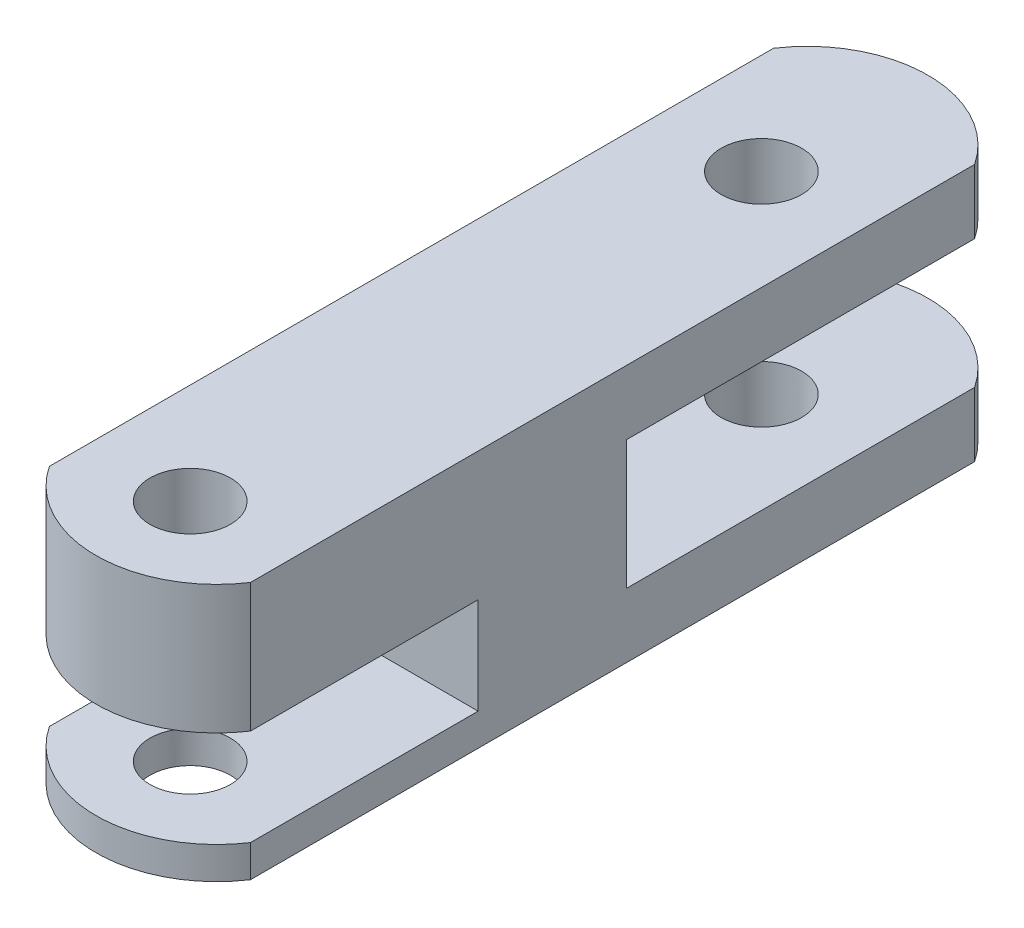
SolidWorks part; units mm, degrees
ref_plane "前视基准面" through (0, 0, 0) normal (0, 0, 1) x (1, 0, 0)
ref_plane "上视基准面" through (0, 0, 0) normal (0, 1, 0) x (1, 0, 0)
ref_plane "右视基准面" through (0, 0, 0) normal (1, 0, 0) x (0, 0, -1)
sketch "草图1" plane through (0, 0, 0) normal (0, 1, 0) x (1, 0, 0)
  line L1 (-12.5, 45) -> (12.5, 45) construction
  line L2 (-12.5, 45) -> (-12.5, -45)
  line L3 (-12.5, -45) -> (12.5, -45) construction
  line L4 (12.5, 45) -> (12.5, -45)
  line L5 (-12.5, 45) -> (12.5, -45) construction
  line L6 (-12.5, -45) -> (12.5, 45) construction
  arc A0 (-12.5, 45) -> (12.5, 45) centre (0, 36.7084) cw
  arc A1 (-12.5, -45) -> (12.5, -45) centre (0, -36.7084) ccw
  point P0 (0, 0)
  dimension "D3" = 15
  dimension "D1" = 90
  dimension "D2" = 25
extrude "凸台-拉伸1" add sketch "草图1" along normal mid plane 32
sketch "草图2" plane through (12.5, 0, 0) normal (1, 0, 0) x (0, 0, -1)
  line L0 (-45, 16) -> (-45, -16) construction
  line L1 (-16.7084, 0) -> (-73.2916, 0)
  line L2 (-16.7084, 0) -> (-16.7084, -12)
  line L3 (-16.7084, -12) -> (-73.2916, -12)
  line L4 (-73.2916, 0) -> (-73.2916, -12)
  line L5 (-16.7084, 0) -> (-73.2916, -12) construction
  line L6 (-16.7084, -12) -> (-73.2916, 0) construction
  line L7 (-45, 16) -> (45, 16) construction
  line L8 (-51.7084, 16) -> (-51.7084, -16) construction
  point P0 (-45, -6)
  dimension "D1" = 12
  dimension "D2" = 16
  dimension "D3" = 35
extrude "切除-拉伸1" cut sketch "草图2" against normal through all
sketch "草图3" plane through (12.5, 0, 0) normal (1, 0, 0) x (0, 0, -1)
  line L0 (45, 16) -> (45, -16) construction
  line L1 (88.2916, 8) -> (1.7084, 8)
  line L2 (88.2916, 8) -> (88.2916, -8)
  line L3 (88.2916, -8) -> (1.7084, -8)
  line L4 (1.7084, 8) -> (1.7084, -8)
  line L5 (88.2916, 8) -> (1.7084, -8) construction
  line L6 (88.2916, -8) -> (1.7084, 8) construction
  line L7 (-45, -16) -> (45, -16) construction
  line L8 (51.7084, -16) -> (51.7084, 16) construction
  point P0 (45, 0)
  dimension "D1" = 8
  dimension "D2" = 50
extrude "切除-拉伸2" cut sketch "草图3" against normal through all
sketch "草图4" plane through (0, 16, 0) normal (0, 1, 0) x (1, 0, 0)
  line L0 (0, 0) -> (0, -40) construction
  line L1 (0, 0) -> (0, 31) construction
  circle A0 centre (0, -40) radius 5
  circle A1 centre (0, 31) radius 5
  dimension "D1" = 10
  dimension "D2" = 40
  dimension "D3" = 31
extrude "切除-拉伸3" cut sketch "草图4" against normal through all
